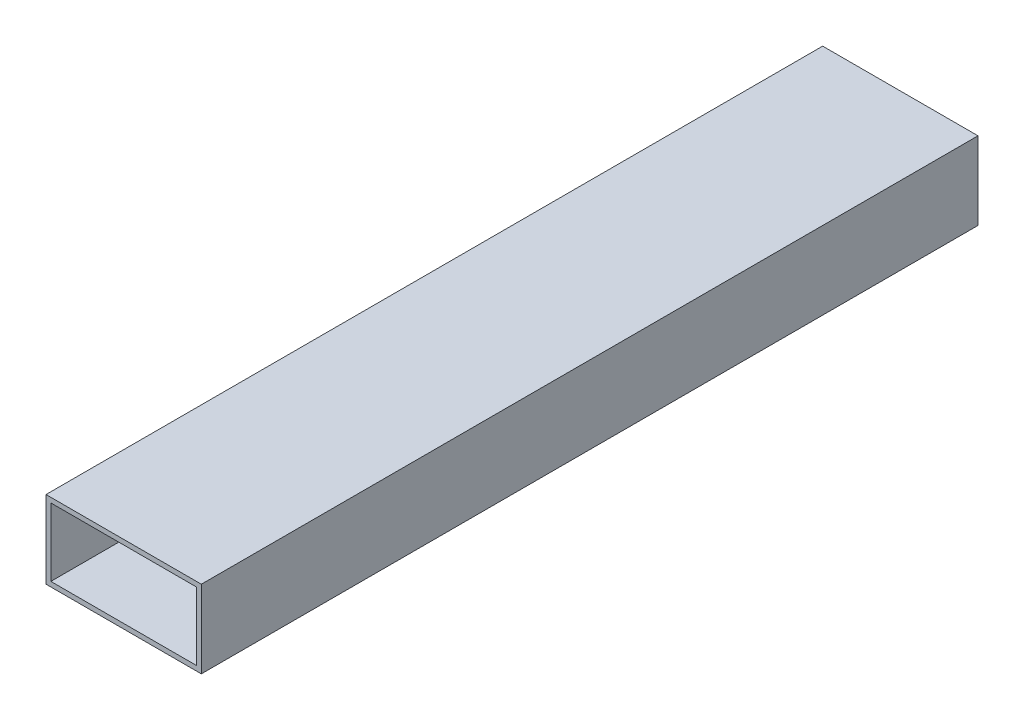
SolidWorks part; units mm, degrees
ref_plane "Front Plane" through (0, 0, 0) normal (0, 0, 1) x (1, 0, 0)
ref_plane "Top Plane" through (0, 0, 0) normal (0, 1, 0) x (1, 0, 0)
ref_plane "Right Plane" through (0, 0, 0) normal (1, 0, 0) x (0, 0, -1)
sketch "Sketch1" plane through (0, 0, 0) normal (0, 0, 1) x (1, 0, 0)
  line L1 (23.8125, -11.1125) -> (-23.8125, -11.1125)
  line L2 (23.8125, -11.1125) -> (23.8125, 11.1125)
  line L3 (23.8125, 11.1125) -> (-23.8125, 11.1125)
  line L4 (-23.8125, -11.1125) -> (-23.8125, 11.1125)
  line L5 (23.8125, -11.1125) -> (-23.8125, 11.1125) construction
  line L6 (23.8125, 11.1125) -> (-23.8125, -11.1125) construction
  line L7 (25.4, -12.7) -> (-25.4, -12.7)
  line L8 (25.4, -12.7) -> (25.4, 12.7)
  line L9 (25.4, 12.7) -> (-25.4, 12.7)
  line L10 (-25.4, -12.7) -> (-25.4, 12.7)
  line L11 (25.4, -12.7) -> (-25.4, 12.7) construction
  line L12 (25.4, 12.7) -> (-25.4, -12.7) construction
  point P0 (0, 0)
  point P6 (0, 0)
  dimension "D1" = 50.8
  dimension "D2" = 25.4
  dimension "D3" = 1.5875
  dimension "D4" = 1.5875
extrude "Boss-Extrude1" add sketch "Sketch1" along normal blind 254
